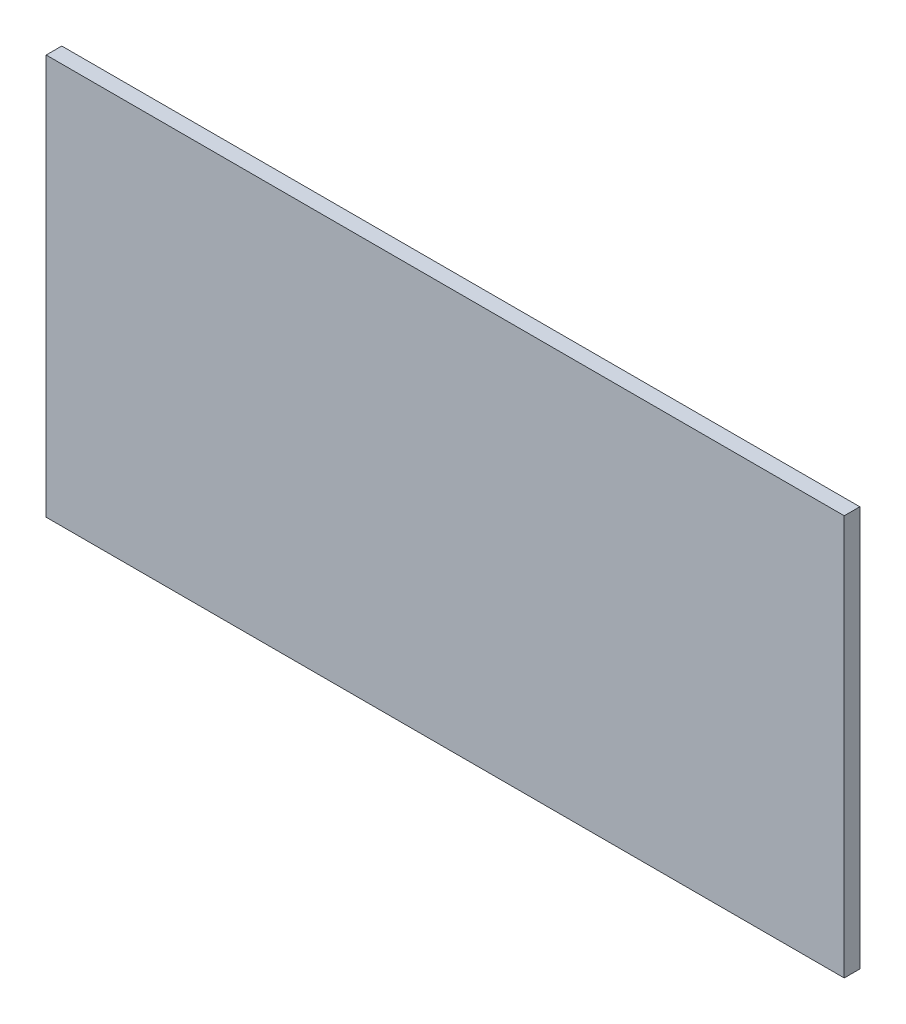
SolidWorks part; units mm, degrees
ref_plane "Спереди" through (0, 0, 0) normal (0, 0, 1) x (1, 0, 0)
ref_plane "Сверху" through (0, 0, 0) normal (0, 1, 0) x (1, 0, 0)
ref_plane "Справа" through (0, 0, 0) normal (1, 0, 0) x (0, 0, -1)
sketch "Эскиз1" plane through (0, 0, 0) normal (0, 0, 1) x (1, 0, 0)
  line L1 (-153.5, 77) -> (153.5, 77)
  line L2 (-153.5, 77) -> (-153.5, -77)
  line L3 (-153.5, -77) -> (153.5, -77)
  line L4 (153.5, 77) -> (153.5, -77)
  line L5 (-153.5, 77) -> (153.5, -77) construction
  line L6 (-153.5, -77) -> (153.5, 77) construction
  point P0 (0, 0)
  dimension "D1" = 154
  dimension "D2" = 307
extrude "Бобышка-Вытянуть1" add sketch "Эскиз1" along normal blind 6
